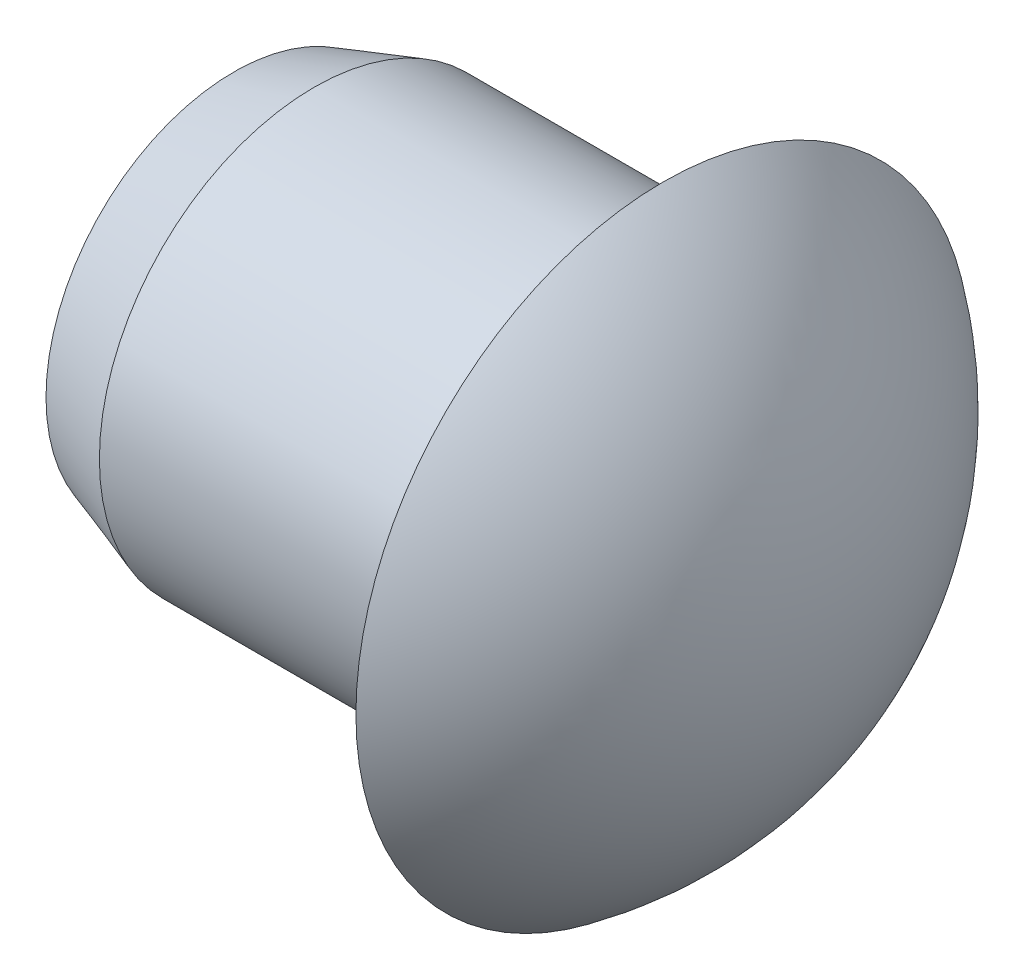
SolidWorks part; units mm, degrees
material "HYPALON"
ref_plane "前视基准面" through (0, 0, 0) normal (0, 0, 1) x (1, 0, 0)
ref_plane "上视基准面" through (0, 0, 0) normal (0, 1, 0) x (1, 0, 0)
ref_plane "右视基准面" through (0, 0, 0) normal (1, 0, 0) x (0, 0, -1)
sketch "草图1" plane through (0, 0, 0) normal (0, 0, 1) x (1, 0, 0)
  line L0 (0, 0) -> (28.3248, 0) construction
  line L1 (0, 2.5) -> (0, 3.5)
  line L2 (0, 3.5) -> (1.4946, 4)
  line L3 (1.4946, 4) -> (8, 4)
  line L4 (8, 4) -> (8, 5.7264)
  line L5 (8, 0) -> (10.9561, 0)
  line L6 (0, 2.5) -> (8, 2.5)
  line L7 (8, 2.5) -> (8, 0)
  arc A0 (8, 5.7264) -> (10.9561, 0) centre (3.9318, 0) cw
  dimension "D1" = 8
  dimension "D4" = 5
  dimension "D2" = 7
  dimension "D3" = 8
  dimension "D5" = 8
revolve "旋转1" add sketch "草图1" angle 360 about L0
